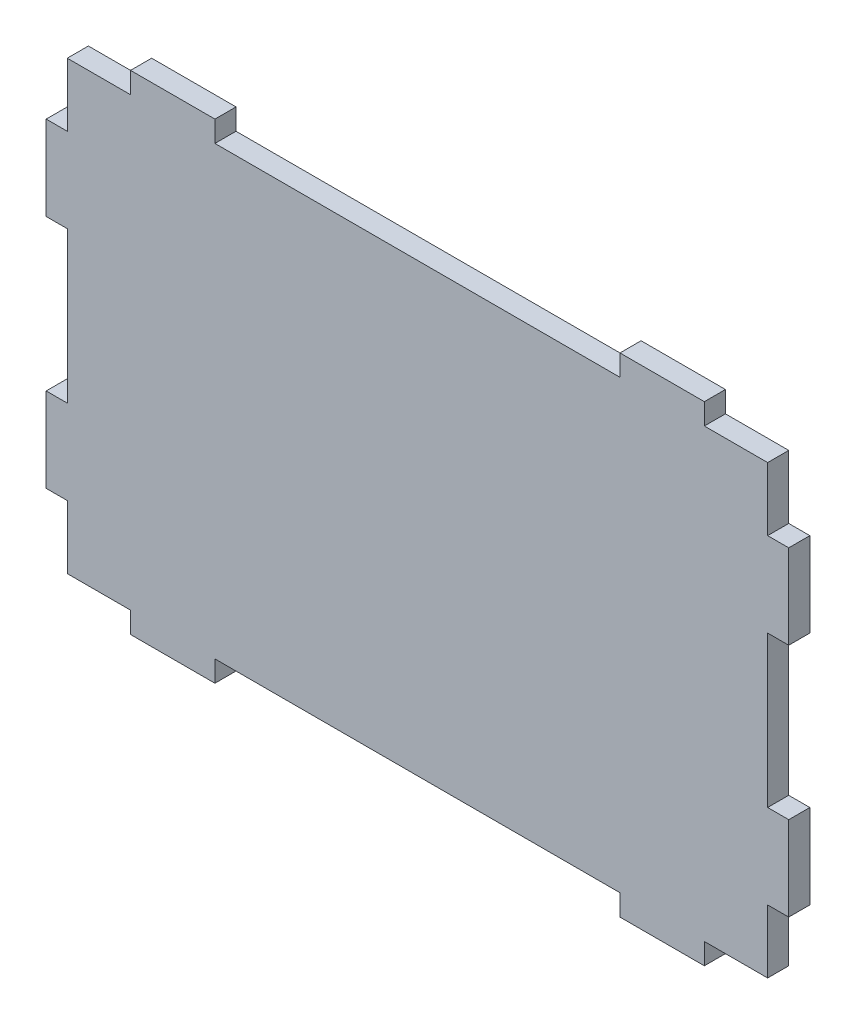
SolidWorks part; units mm, degrees
ref_plane "Alzado" through (0, 0, 0) normal (0, 0, 1) x (1, 0, 0)
ref_plane "Planta" through (0, 0, 0) normal (0, 1, 0) x (1, 0, 0)
ref_plane "Vista lateral" through (0, 0, 0) normal (1, 0, 0) x (0, 0, -1)
sketch "Croquis1" plane through (0, 0, 0) normal (0, 0, 1) x (1, 0, 0)
  line L0 (80.799, 65.9379) -> (60.799, 65.9379)
  line L1 (60.799, 65.9379) -> (60.799, 60.9379)
  line L3 (80.799, 60.9379) -> (80.799, 65.9379)
  line L5 (95.799, -29.8621) -> (100.799, -29.8621)
  line L6 (100.799, -29.8621) -> (100.799, -9.8621)
  line L7 (100.799, -9.8621) -> (95.799, -9.8621)
  line L9 (95.799, 25.9379) -> (100.799, 25.9379)
  line L10 (100.799, 25.9379) -> (100.799, 45.9379)
  line L11 (100.799, 45.9379) -> (95.799, 45.9379)
  line L13 (60.799, -44.8621) -> (60.799, -49.8621)
  line L14 (60.799, -49.8621) -> (80.799, -49.8621)
  line L15 (80.799, -49.8621) -> (80.799, -44.8621)
  line L17 (-55.201, -44.8621) -> (-55.201, -49.8621)
  line L18 (-55.201, -49.8621) -> (-35.201, -49.8621)
  line L19 (-35.201, -49.8621) -> (-35.201, -44.8621)
  line L21 (-70.201, -9.8621) -> (-75.201, -9.8621)
  line L22 (-75.201, -9.8621) -> (-75.201, -29.8621)
  line L23 (-75.201, -29.8621) -> (-70.201, -29.8621)
  line L25 (-70.201, 45.9379) -> (-75.201, 45.9379)
  line L26 (-75.201, 45.9379) -> (-75.201, 25.9379)
  line L27 (-75.201, 25.9379) -> (-70.201, 25.9379)
  line L28 (-35.201, 65.9379) -> (-55.201, 65.9379)
  line L29 (-55.201, 65.9379) -> (-55.201, 60.9379)
  line L31 (-35.201, 60.9379) -> (-35.201, 65.9379)
  line L32 (-70.201, 60.9379) -> (-70.201, 45.9379)
  line L33 (-70.201, -44.8621) -> (-55.201, -44.8621)
  line L34 (95.799, -44.8621) -> (95.799, -29.8621)
  line L35 (95.799, 60.9379) -> (80.799, 60.9379)
  line L36 (-55.201, 60.9379) -> (-70.201, 60.9379)
  line L37 (-70.201, 25.9379) -> (-70.201, -9.8621)
  line L38 (-35.201, -44.8621) -> (60.799, -44.8621)
  line L39 (80.799, -44.8621) -> (95.799, -44.8621)
  line L40 (95.799, -9.8621) -> (95.799, 25.9379)
  line L41 (95.799, 45.9379) -> (95.799, 60.9379)
  line L42 (60.799, 60.9379) -> (-35.201, 60.9379)
  line L43 (-70.201, -29.8621) -> (-70.201, -44.8621)
extrude "Saliente-Extruir1" add sketch "Croquis1" along normal blind 5
